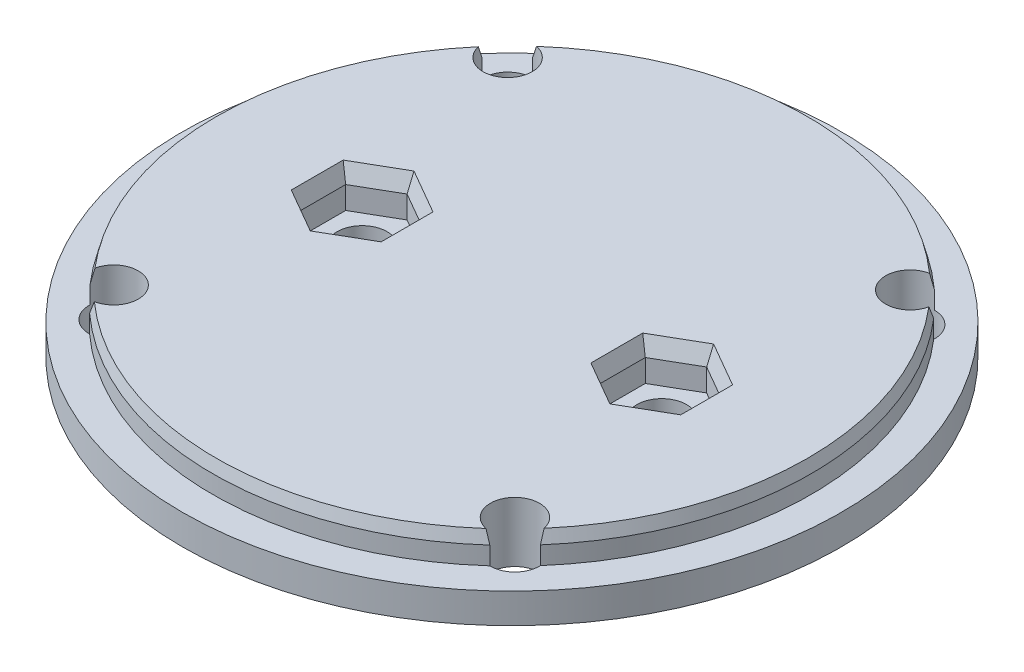
SolidWorks part; units mm, degrees
ref_plane "Спереди" through (0, 0, 0) normal (0, 0, 1) x (1, 0, 0)
ref_plane "Сверху" through (0, 0, 0) normal (0, 1, 0) x (1, 0, 0)
ref_plane "Справа" through (0, 0, 0) normal (1, 0, 0) x (0, 0, -1)
sketch "Эскиз1" plane through (0, 0, 0) normal (0, 1, 0) x (1, 0, 0)
  circle A0 centre (0, 0) radius 55
  dimension "D1" = 110
extrude "Бобышка-Вытянуть1" add sketch "Эскиз1" along normal blind 5
sketch "Эскиз2" plane through (0, 5, 0) normal (0, 1, 0) x (1, 0, 0)
  circle A0 centre (0, 0) radius 49.9
  dimension "D1" = 99.8
extrude "Бобышка-Вытянуть2" add sketch "Эскиз2" along normal blind 5
sketch "Эскиз3" plane through (0, 0, 0) normal (0, -1, 0) x (1, 0, 0)
  line L1 (17.5, -15) -> (-17.5, -15)
  line L2 (17.5, -15) -> (17.5, 15)
  line L3 (17.5, 15) -> (-17.5, 15)
  line L4 (-17.5, -15) -> (-17.5, 15)
  line L5 (17.5, -15) -> (-17.5, 15) construction
  line L6 (17.5, 15) -> (-17.5, -15) construction
  point P0 (0, 0)
  dimension "D1" = 35
  dimension "D2" = 30
extrude "Бобышка-Вытянуть3" add sketch "Эскиз3" along normal blind 25
sketch "Эскиз4" plane through (0, 0, 15) normal (0, 0, 1) x (1, 0, 0)
  line L0 (-17.5, 0) -> (17.5, -25) construction
  line L2 (10.1, -17.65) -> (-10.1, -17.65)
  line L3 (10.1, -17.65) -> (10.1, -7.35)
  line L4 (10.1, -7.35) -> (-10.1, -7.35)
  line L5 (-10.1, -17.65) -> (-10.1, -7.35)
  line L6 (10.1, -17.65) -> (-10.1, -7.35) construction
  line L7 (10.1, -7.35) -> (-10.1, -17.65) construction
  point P4 (0, -12.5)
  dimension "D1" = 20.2
  dimension "D2" = 10.3
extrude "Вырез-Вытянуть1" cut sketch "Эскиз4" against normal through all
sketch "Эскиз5" plane through (0, 0, 0) normal (0, -1, 0) x (1, 0, 0)
  line L0 (23.35, -22.85) -> (39.3102, -38.467) construction
  line L5 (-23.35, 22.85) -> (23.35, -22.85) construction
  line L6 (-23.35, -22.85) -> (23.35, 22.85) construction
  line L7 (-23.35, 22.85) -> (-39.3095, 38.4677) construction
  line L8 (23.35, 22.85) -> (39.1401, 38.6401) construction
  line L9 (-23.35, -22.85) -> (-39.3095, -38.4677) construction
  circle A0 centre (0, 0) radius 55 construction
  circle A1 centre (33.5922, -32.8719) radius 4.1
  circle A2 centre (-33.5917, -32.8724) radius 4.1
  circle A3 centre (-33.5917, 32.8724) radius 4.1
  circle A4 centre (33.4832, 32.9832) radius 4.1
  point P0 (0, 0)
  dimension "D3" = 8.2
  dimension "D1" = 46.7
  dimension "D2" = 45.7
  dimension "D4" = 8
  dimension "D5" = 8
  dimension "D6" = 8
  dimension "D7" = 8
extrude "Вырез-Вытянуть2" cut sketch "Эскиз5" against normal through all
chamfer "Chamfer1" distance 2 angle 15 4 edges at (-0.0824, 10, 49.8999) (-49.9, 10, 0) (0.0004, 10, -49.9) (49.8999, 10, 0.0826)
sketch "Sketch2" plane through (0, -25, 0) normal (0, -1, 0) x (1, 0, 0)
  line L0 (17.5, 0) -> (-17.5, 0) construction
  line L1 (17.5, -15) -> (17.5, 15) construction
  line L2 (-17.5, 15) -> (-17.5, -15) construction
  line L4 (-17.5, -15) -> (17.5, -15)
  line L5 (-17.5, -15) -> (-17.5, 15)
  line L6 (-17.5, 15) -> (17.5, 15)
  line L7 (17.5, -15) -> (17.5, 15)
  line L8 (-17.5, -15) -> (17.5, 15) construction
  line L9 (-17.5, 15) -> (17.5, -15) construction
  point P6 (0, 0)
extrude "Cut-Extrude1" cut sketch "Sketch2" against normal blind 12.5
sketch "Sketch4" plane through (0, -7.35, 0) normal (0, -1, 0) x (1, 0, 0)
  line L1 (-35, -10) -> (35, -10)
  line L2 (-35, -10) -> (-35, 10)
  line L3 (-35, 10) -> (35, 10)
  line L4 (35, -10) -> (35, 10)
  line L5 (-35, -10) -> (35, 10) construction
  line L6 (-35, 10) -> (35, -10) construction
  point P0 (0, 0)
  dimension "D1" = 20
  dimension "D2" = 70
extrude "Boss-Extrude1" add sketch "Sketch4" against normal up to surface (5.35 mm away) from offset 2 up to face at (-33.5917, 0, -36.9724) offset against normal yes
sketch "Sketch5" plane through (0, -5.35, 0) normal (0, -1, 0) x (1, 0, 0)
  line L0 (25, 10) -> (25, -10) construction
  line L1 (35, 10) -> (17.5, 10) construction
  line L2 (17.5, -10) -> (35, -10) construction
  line L3 (-25, 10) -> (-25, -10) construction
  line L4 (-17.5, 10) -> (-35, 10) construction
  line L5 (-35, -10) -> (-17.5, -10) construction
  circle A0 centre (25, 0) radius 4.15
  circle A1 centre (-25, 0) radius 4.15
  dimension "D1" = 8.3
  dimension "D2" = 50
  dimension "D3" = 25
extrude "Cut-Extrude2" cut sketch "Sketch5" against normal through all
sketch "Sketch6" plane through (0, 10, 0) normal (0, 1, 0) x (1, 0, 0)
  line L1 (-18.5048, 3.75) -> (-25, 7.5)
  line L2 (-25, 7.5) -> (-31.4952, 3.75)
  line L3 (-31.4952, 3.75) -> (-31.4952, -3.75)
  line L4 (-31.4952, -3.75) -> (-25, -7.5)
  line L5 (-25, -7.5) -> (-18.5048, -3.75)
  line L6 (-18.5048, -3.75) -> (-18.5048, 3.75)
  line L7 (31.4952, 3.75) -> (25, 7.5)
  line L8 (25, 7.5) -> (18.5048, 3.75)
  line L9 (18.5048, 3.75) -> (18.5048, -3.75)
  line L10 (18.5048, -3.75) -> (25, -7.5)
  line L11 (25, -7.5) -> (31.4952, -3.75)
  line L12 (31.4952, -3.75) -> (31.4952, 3.75)
  circle A0 centre (-25, 0) radius 7.5 construction
  circle A1 centre (25, 0) radius 7.5 construction
  dimension "D1" = 15
extrude "Cut-Extrude3" cut sketch "Sketch6" against normal blind 6.5
chamfer "Chamfer2" distance 1 angle 70 12 edges at (-28.2476, 10, -5.625) (-31.4952, 10, 0) (-28.2476, 10, 5.625) (-21.7524, 10, 5.625) (-18.5048, 10, 0) (-21.7524, 10, -5.625) (18.5048, 10, 0) (21.7524, 10, 5.625) (28.2476, 10, 5.625) (31.4952, 10, 0) (28.2476, 10, -5.625) (21.7524, 10, -5.625)
